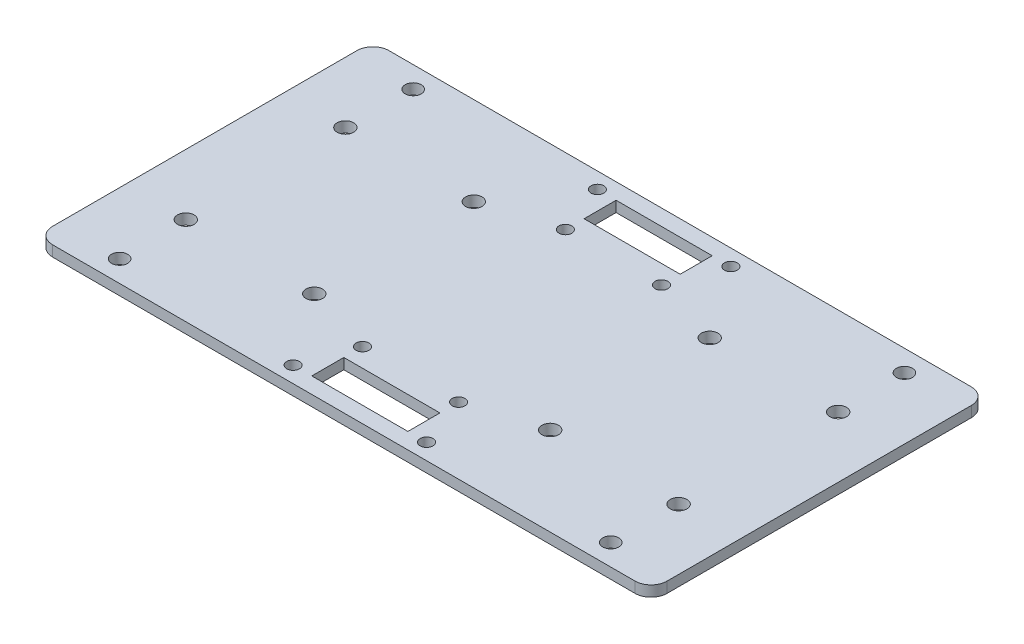
SolidWorks part; units mm, degrees
ref_plane "Plano frontal" through (0, 0, 0) normal (0, 0, 1) x (1, 0, 0)
ref_plane "Plano superior" through (0, 0, 0) normal (0, 1, 0) x (1, 0, 0)
ref_plane "Plano direito" through (0, 0, 0) normal (1, 0, 0) x (0, 0, -1)
sketch "Esboço1" plane through (0, 0, 0) normal (0, 1, 0) x (1, 0, 0)
  line L7 (-57.5484, 31.5) -> (57.5484, 31.5)
  line L8 (57.5484, 31.5) -> (57.5484, -31.5)
  line L9 (57.5484, -31.5) -> (-57.5484, -31.5)
  line L10 (-57.5484, -31.5) -> (-57.5484, 31.5)
  line L11 (0, 31.5) -> (0, -31.5) construction
  line L12 (-57.5484, 0) -> (57.5484, 0) construction
  dimension "D1" = 63
  dimension "D2" = 115.0968
extrude "Ressalto-extrusão1" add sketch "Esboço1" along normal blind 2
sketch "Esboço2" plane through (0, 2, 0) normal (0, 1, 0) x (1, 0, 0)
  line L0 (-57.5484, 0) -> (57.5484, 0) construction
  line L1 (-57.5484, 31.5) -> (-57.5484, -31.5) construction
  line L2 (-57.5484, -31.5) -> (57.5484, -31.5) construction
  line L5 (57.5484, -31.5) -> (57.5484, 31.5) construction
  line L6 (0, -31.5) -> (0, 31.5) construction
  line L7 (57.5484, 31.5) -> (-57.5484, 31.5) construction
  circle A8 centre (-46.1536, -14.945) radius 1.55
  circle A10 centre (-22.0936, -14.94) radius 1.55
  circle A11 centre (22.0936, -14.94) radius 1.55
  circle A12 centre (46.1536, -14.945) radius 1.55
  circle A13 centre (46.1536, 14.945) radius 1.55
  circle A14 centre (22.0936, 14.94) radius 1.55
  circle A15 centre (-22.0936, 14.94) radius 1.55
  circle A16 centre (-46.1536, 14.945) radius 1.55
  dimension "D1" = 16.555
  dimension "D3" = 3.1
  dimension "D4" = 16.56
  dimension "D2" = 24.06
  dimension "D5" = 11.3948
extrude "Corte-extrusão1" cut sketch "Esboço2" against normal through all
sketch "Esboço3" plane through (0, 0, 0) normal (0, -1, 0) x (1, 0, 0)
  line L0 (0, 31.5) -> (0, 28.5) construction
  line L1 (-57.5484, 31.5) -> (57.5484, 31.5) construction
  line L2 (-9, 28.5) -> (9, 28.5)
  line L3 (9, 28.5) -> (9, 22.5)
  line L4 (-9, 28.5) -> (-9, 22.5)
  line L5 (-9, 22.5) -> (9, 22.5)
  line L6 (-57.5484, 0) -> (57.5484, 0) construction
  line L7 (-57.5484, -31.5) -> (-57.5484, 31.5) construction
  line L8 (57.5484, 31.5) -> (57.5484, -31.5) construction
  line L9 (9, 28.5) -> (9, 22.5)
  line L10 (-9, 28.5) -> (-9, 22.5)
  line L11 (9, 28.5) -> (9, 22.5)
  line L12 (-9, 28.5) -> (-9, 22.5)
  line L13 (9, 28.5) -> (9, 22.5)
  line L14 (-9, 28.5) -> (-9, 22.5)
  line L15 (0, -31.5) -> (0, -28.5) construction
  line L16 (-9, -28.5) -> (-9, -22.5)
  line L17 (9, -28.5) -> (9, -22.5)
  line L18 (-9, -28.5) -> (-9, -22.5)
  line L19 (9, -28.5) -> (9, -22.5)
  line L20 (-9, -28.5) -> (-9, -22.5)
  line L21 (9, -28.5) -> (9, -22.5)
  line L22 (-9, -22.5) -> (9, -22.5)
  line L23 (-9, -28.5) -> (-9, -22.5)
  line L24 (9, -28.5) -> (9, -22.5)
  line L25 (-9, -28.5) -> (9, -28.5)
  point P8 (0, 28.5)
  point P22 (0, -28.5)
  dimension "D1" = 3
  dimension "D2" = 18
  dimension "D3" = 6
extrude "Corte-extrusão2" cut sketch "Esboço3" against normal through all contours L4 L5 L3 L2 | L16 L25 L17 L22
fillet "Filete1" radius 3 4 edges at (57.5484, 1, -31.5) (57.5484, 1, 31.5) (-57.5484, 1, 31.5) (-57.5484, 1, -31.5)
sketch "Esboço8" plane through (0, 2, 0) normal (0, 1, 0) x (1, 0, 0)
  line L0 (-57.5484, 28.5) -> (-57.5484, -28.5) construction
  line L1 (54.5484, 31.5) -> (-54.5484, 31.5) construction
  line L2 (0, 0) -> (0, 31.5) construction
  line L3 (57.5484, 0) -> (-57.5484, 0) construction
  line L4 (-54.5484, -31.5) -> (54.5484, -31.5) construction
  line L5 (57.5484, -28.5) -> (57.5484, 28.5) construction
  circle A0 centre (-12.4984, 28.5) radius 1.2
  circle A1 centre (12.4984, 28.5) radius 1.2
  circle A2 centre (12.4984, -28.5) radius 1.2
  circle A3 centre (-12.4984, -28.5) radius 1.2
  circle A8 centre (-8.9984, -19) radius 1.2
  circle A12 centre (8.9984, -19) radius 1.2
  circle A13 centre (8.9984, 19) radius 1.2
  circle A14 centre (-8.9984, 19) radius 1.2
  dimension "D1" = 2.4
  dimension "D4" = 2.4
  dimension "D5" = 12.5
  dimension "D6" = 48.55
  dimension "D2" = 45.05
  dimension "D3" = 3
extrude "Corte-extrusão4" cut sketch "Esboço8" against normal through all
sketch "Esboço9" plane through (0, 2, 0) normal (0, 1, 0) x (1, 0, 0)
  line L5 (-57.5484, 28.5) -> (-57.5484, -28.5) construction
  line L6 (54.5484, 31.5) -> (-54.5484, 31.5) construction
  line L7 (0, 0) -> (0, 31.5) construction
  line L8 (0, 0) -> (50, 0) construction
  circle A0 centre (-46, 27.5) radius 1.5
  circle A4 centre (46, 27.5) radius 1.5
  circle A5 centre (46, -27.5) radius 1.5
  circle A6 centre (-46, -27.5) radius 1.5
  point P0 (0, 0)
  dimension "D2" = 3
  dimension "D1" = 11.5484
  dimension "D3" = 4
extrude "Corte-extrusão5" cut sketch "Esboço9" against normal through all
